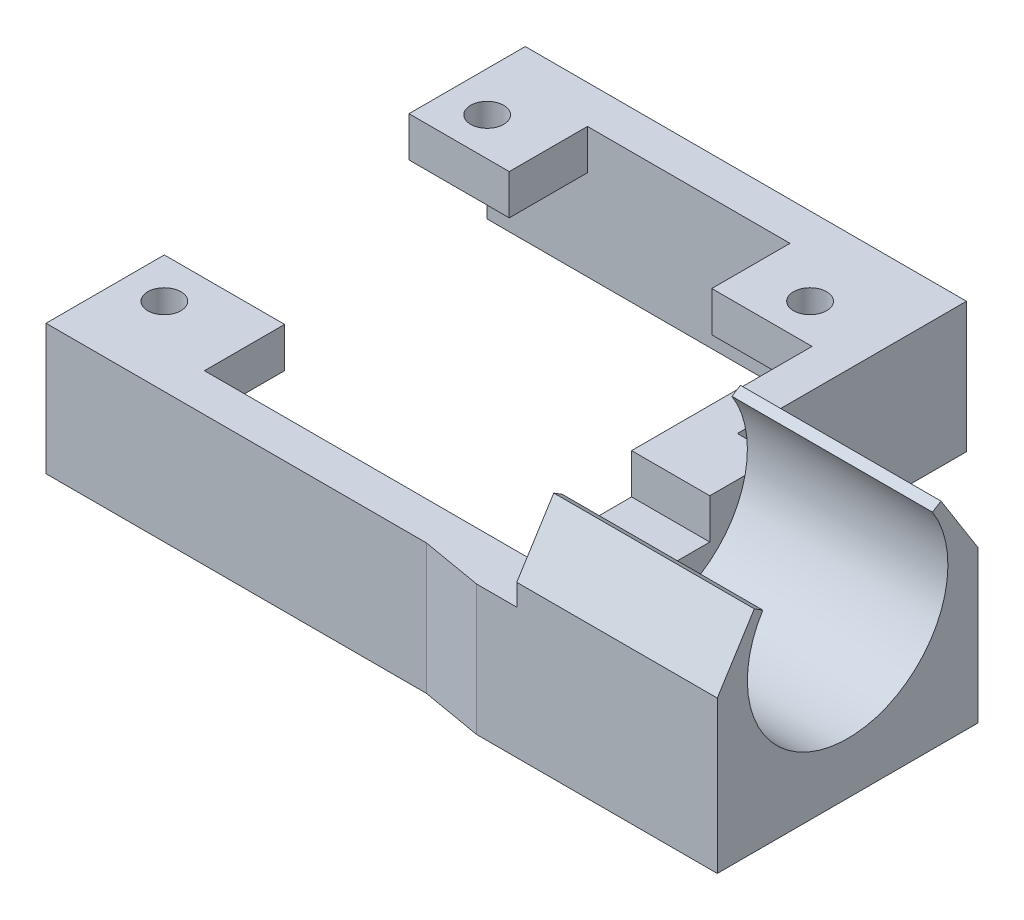
SolidWorks part; units mm, degrees
ref_plane "Front Plane" through (0, 0, 0) normal (0, 0, 1) x (1, 0, 0)
ref_plane "Top Plane" through (0, 0, 0) normal (0, 1, 0) x (1, 0, 0)
ref_plane "Right Plane" through (0, 0, 0) normal (1, 0, 0) x (0, 0, -1)
sketch "Sketch1" plane through (0, 0, 0) normal (0, 1, 0) x (1, 0, 0)
  line L0 (-20.1, 20.1) -> (20.1, -20.1) construction
  line L1 (-20.1, 20.1) -> (20.1, 20.1)
  line L3 (-20.1, -20.1) -> (20.1, -20.1)
  line L4 (20.1, 20.1) -> (20.1, -20.1)
  line L5 (-20.1, -20.1) -> (20.1, 20.1) construction
  line L7 (-20.1, -23.9) -> (23.9, -23.9)
  line L8 (23.9, 23.9) -> (23.9, -23.9)
  line L9 (-20.1, 23.9) -> (23.9, 23.9)
  line L10 (-20.1, 20.1) -> (-20.1, -20.1) construction
  line L11 (-23.9, 23.9) -> (-23.9, -23.9) construction
  line L12 (-20.1, 20.1) -> (-20.1, 23.9)
  line L13 (-20.1, -20.1) -> (-20.1, -23.9)
  line L14 (-23.9, 23.9) -> (23.9, 23.9) construction
  line L15 (-23.9, -23.9) -> (23.9, -23.9) construction
  point P4 (0, 0)
  dimension "D1" = 40.2
  dimension "D2" = 40.2
  dimension "D3" = 3.8
extrude "Boss-Extrude1" add sketch "Sketch1" along normal blind 9
sketch "Sketch10" plane through (23.9, 0, 0) normal (1, 0, 0) x (0, 0, -1)
  line L0 (-23.9, 9) -> (23.9, 9) construction
  line L1 (-5.8, 28.48) -> (-19.8, 28.48) construction
  line L2 (-5.8, 28.48) -> (-5.8, 9) construction
  line L3 (-5.8, 9) -> (-19.8, 9) construction
  line L4 (-19.8, 28.48) -> (-19.8, 9) construction
  line L7 (-24.95, 15.15) -> (-24.95, 0)
  line L8 (-24.95, 15.15) -> (-21.2577, 21.0123)
  line L9 (-24.95, 0) -> (-23.9, 0)
  line L10 (-23.9, 0) -> (1.05, 0)
  line L11 (-23.9, 0) -> (23.9, 0) construction
  line L12 (1.05, 0) -> (1.05, 15.15)
  line L13 (1.05, 15.15) -> (-2.6423, 21.0123)
  line L14 (-21.2577, 21.0123) -> (-20.4115, 20.4794)
  line L15 (-2.6423, 21.0123) -> (-3.4885, 20.4794)
  arc A0 (-20.4115, 20.4794) -> (-3.4885, 20.4794) centre (-11.95, 15.15) ccw
  arc A1 (-21.2577, 21.0123) -> (-2.6423, 21.0123) centre (-11.95, 15.15) ccw
  circle A2 centre (-11.95, 15.15) radius 5.15 construction
  line M4 (-23.9, 0) -> (23.9, 0)
  line M6 (23.9, 9) -> (-23.9, 9)
  line M7 (-23.9, 9) -> (-23.9, 0)
  dimension "D1" = 20
  dimension "D2" = 22
  dimension "D3" = 10.3
  dimension "D5" = 6.15
  dimension "D4" = 14
  dimension "D6" = 6.15
  dimension "D7" = 0.3
  dimension "D8" = 13.33
  dimension "D9" = 13
sketch "Sketch11" plane through (23.9, 0, 0) normal (1, 0, 0) x (0, 0, -1)
  line L0 (-24.95, 15.15) -> (-24.95, 0) construction
  line L1 (1.05, 0) -> (-24.95, 0)
  line L2 (1.05, 0) -> (1.05, 9)
  line L3 (1.05, 9) -> (-24.95, 9)
  line L4 (-24.95, 0) -> (-24.95, 9)
  line L5 (-5.8, 9) -> (-19.8, 9) construction
extrude "Boss-Extrude2" add sketch "Sketch11" along normal blind 4
extrude "Boss-Extrude3" add sketch "Sketch10" along normal blind 20 from surface at 4 contours A1 L8 L7 L9 M7 | A1 L12 M7 M4 M6 | A1 L12 L13 M6 | A1 A0 M7 M6 | A1 A0 M7 M6 | A1 L15 A0 M6
sketch "Sketch12" plane through (0, 9, 0) normal (0, 1, 0) x (1, 0, 0)
  line L0 (23.9, -24.95) -> (17.8294, -23.9)
  line L1 (-20.1, -23.9) -> (23.9, -23.9) construction
  line L2 (17.8294, -23.9) -> (23.9, -23.9)
  line L3 (23.9, -23.9) -> (23.9, -24.95)
extrude "Boss-Extrude4" add sketch "Sketch12" against normal up to surface (9 mm away) up to face at (12.6, 0, 3.9833)
sketch "Sketch13" plane through (0, 9, 0) normal (0, 1, 0) x (1, 0, 0)
  line L0 (-20.1, -23.9) -> (17.8294, -23.9) construction
  line L1 (-20.1, -20.1) -> (-8.1, -20.1)
  line L2 (-20.1, -20.1) -> (-20.1, -12.1)
  line L3 (-20.1, -12.1) -> (-8.1, -12.1)
  line L4 (-8.1, -20.1) -> (-8.1, -12.1)
  line L5 (-20.1, -20.1) -> (-8.1, -20.1)
  line L6 (-20.1, -20.1) -> (-20.1, -23.9)
  line L7 (-20.1, -23.9) -> (-8.1, -23.9)
  line L8 (-8.1, -20.1) -> (-8.1, -23.9)
  line L9 (-20.1, 20.1) -> (20.1, 20.1) construction
  line L10 (23.9, 23.9) -> (10.1, 23.9)
  line L11 (23.9, 23.9) -> (23.9, 12.3)
  line L12 (23.9, 12.3) -> (10.1, 12.3)
  line L13 (10.1, 23.9) -> (10.1, 12.3)
  line L14 (-20.1, 23.9) -> (-10.1, 23.9)
  line L15 (-20.1, 23.9) -> (-20.1, 12.3)
  line L16 (-20.1, 12.3) -> (-10.1, 12.3)
  line L17 (-10.1, 23.9) -> (-10.1, 12.3)
  line L18 (20.1, 20.1) -> (20.1, -20.1) construction
  line L19 (27.9, -19.8353) -> (27.9, -4.0647) construction
  line L20 (-8.1, -23.9) -> (27.9, -23.9)
  line L21 (-8.1, -23.9) -> (-8.1, -20.1)
  line L22 (-8.1, -20.1) -> (27.9, -20.1)
  line L23 (27.9, -23.9) -> (27.9, -20.1)
  line L24 (27.9, 1.05) -> (27.9, -4.0647) construction
  line L25 (-10.1, 23.9) -> (10.1, 23.9)
  line L26 (-10.1, 23.9) -> (-10.1, 20.1)
  line L27 (-10.1, 20.1) -> (10.1, 20.1)
  line L28 (10.1, 23.9) -> (10.1, 20.1)
  line L29 (23.9, 12.3) -> (20.1, 12.3)
  line L30 (23.9, 12.3) -> (23.9, -5.7)
  line L31 (23.9, -5.7) -> (20.1, -5.7)
  line L32 (20.1, 12.3) -> (20.1, -5.7)
  line L33 (23.9, 1.05) -> (27.9, 1.05)
  line L34 (23.9, 1.05) -> (23.9, -5.7)
  line L35 (23.9, -5.7) -> (27.9, -5.7)
  line L36 (27.9, 1.05) -> (27.9, -5.7)
  line L37 (17.8294, -23.9) -> (23.9, -24.95)
  line L38 (23.9, -24.95) -> (27.9, -24.95)
  line L39 (27.9, -24.95) -> (27.9, -23.9)
  circle A0 centre (-16.1, -16.1) radius 1.65
  circle A1 centre (-16.1, 16.1) radius 1.65
  circle A2 centre (16.1, 16.1) radius 1.65
  line M17 (-20.1, -23.9) -> (17.8294, -23.9)
  line M18 (17.8294, -23.9) -> (23.9, -24.95)
  line M19 (23.9, -24.95) -> (27.9, -24.95)
  line M20 (27.9, -24.95) -> (27.9, -19.8353)
  line M21 (27.9, -19.8353) -> (27.9, -4.0647)
  line M22 (27.9, -4.0647) -> (27.9, 1.05)
  line M23 (27.9, 1.05) -> (23.9, 1.05)
  line M24 (23.9, 1.05) -> (23.9, 23.9)
  line M25 (23.9, 23.9) -> (-20.1, 23.9)
  line M26 (-20.1, 23.9) -> (-20.1, 20.1)
  line M27 (-20.1, 20.1) -> (20.1, 20.1)
  line M28 (20.1, 20.1) -> (20.1, -20.1)
  line M29 (20.1, -20.1) -> (-20.1, -20.1)
  line M30 (-20.1, -20.1) -> (-20.1, -23.9)
  dimension "D12" = 3.3
  dimension "D13" = 3.3
  dimension "D14" = 3.3
  dimension "D1" = 12
  dimension "D2" = 8
  dimension "D3" = 7.8
  dimension "D4" = 10
  dimension "D5" = 10
  dimension "D6" = 4
  dimension "D7" = 4
  dimension "D8" = 4
  dimension "D9" = 4
  dimension "D10" = 4
  dimension "D11" = 4
  dimension "D15" = 14.4
extrude "Boss-Extrude5" add sketch "Sketch13" along normal blind 4 contours L4 L3 L2 M29 | L8 M29 M30 M17 | L17 L15 L16 M27 | L17 M25 M26 M27 | L13 L12 M25 M27 M28 M24 | L13 L12 M27 M28 | L22 L8 L20 M29 M17 M20 M21 | L31 L30 L12 M24 M28 | L30 L35 M22 M23 | L17 L13 M25 M27 | L20 M18 M19 M20
